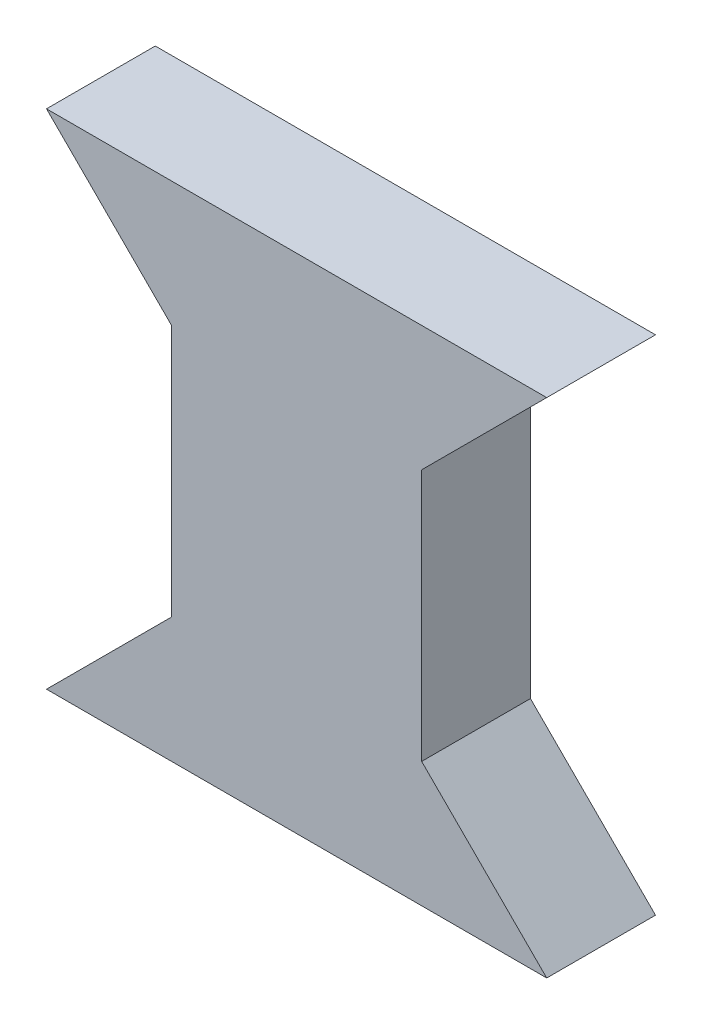
SolidWorks part; units mm, degrees
ref_plane "Спереди" through (0, 0, 0) normal (0, 0, 1) x (1, 0, 0)
ref_plane "Сверху" through (0, 0, 0) normal (0, 1, 0) x (1, 0, 0)
ref_plane "Справа" through (0, 0, 0) normal (1, 0, 0) x (0, 0, -1)
sketch "Эскиз1" plane through (0, 0, 0) normal (0, 0, 1) x (1, 0, 0)
  line L0 (0, 41.3787) -> (0, -37.7238) construction
  line L1 (-75.9889, 1.8274) -> (58.198, 1.8274) construction
  line L2 (22.9929, 24.9316) -> (-22.9929, 24.9316)
  line L3 (-22.9929, 24.9316) -> (-11.4965, 13.4352)
  line L4 (-11.4965, 13.4352) -> (-11.4965, -9.7803)
  line L5 (11.4965, 13.4352) -> (11.4965, -9.7803)
  line L6 (22.9929, 24.9316) -> (11.4965, 13.4352)
  line L7 (22.9929, -21.2767) -> (11.4965, -9.7803)
  line L8 (-22.9929, -21.2767) -> (-11.4965, -9.7803)
  line L9 (22.9929, -21.2767) -> (-22.9929, -21.2767)
  point P4 (0, -21.2767)
  point P12 (0, 24.9316)
  point P15 (11.4965, 1.8274)
  point P16 (-11.4965, 1.8274)
extrude "Бобышка-Вытянуть1" add sketch "Эскиз1" along normal blind 10
